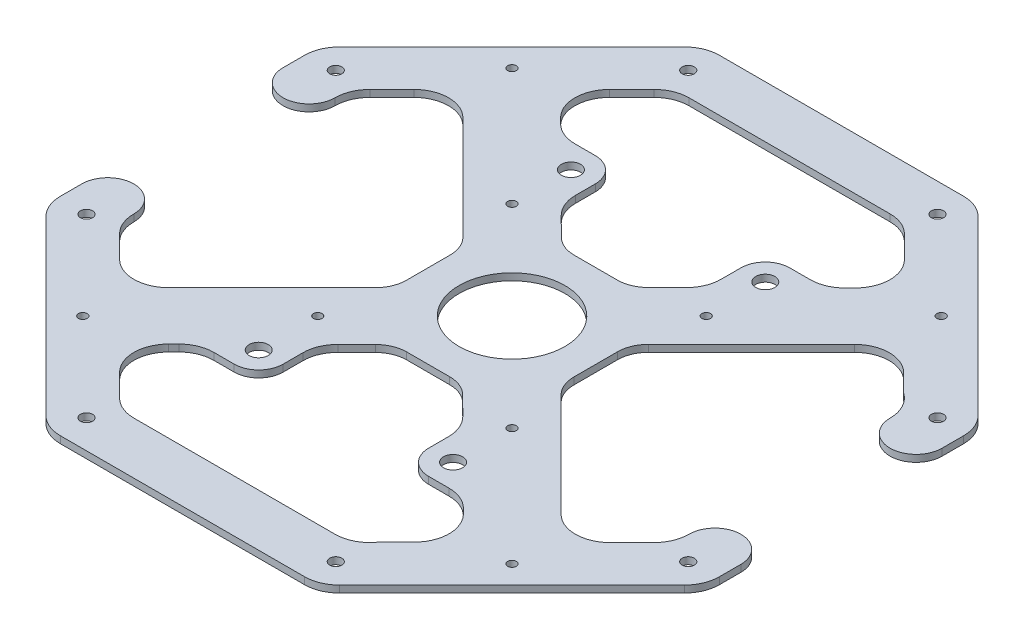
SolidWorks part; units mm, degrees
material "Hexcel AS4C (3000 Filaments)"
ref_plane "Front Plane" through (0, 0, 0) normal (0, 0, 1) x (1, 0, 0)
ref_plane "Top Plane" through (0, 0, 0) normal (0, 1, 0) x (1, 0, 0)
ref_plane "Right Plane" through (0, 0, 0) normal (1, 0, 0) x (0, 0, -1)
sketch "Sketch2" plane through (0, 0, 0) normal (0, 1, 0) x (1, 0, 0)
  line L0 (42.4939, 70.6432) -> (36.066, 77.0711)
  line L1 (92.0711, 42.2792) -> (42.2792, 92.0711)
  line L2 (35.2082, 95) -> (-35.2082, 95)
  line L3 (-42.2792, 92.0711) -> (-92.0711, 42.2792)
  line L4 (-95, 35.2082) -> (-95, -35.2082)
  line L5 (-92.0711, -42.2792) -> (-42.2792, -92.0711)
  line L6 (-35.2082, -95) -> (35.2082, -95)
  line L7 (42.2792, -92.0711) -> (92.0711, -42.2792)
  line L8 (95, -35.2082) -> (95, 35.2082)
  line L9 (28.9949, 80) -> (-28.9949, 80)
  line L10 (-70.7107, 42.4264) -> (-77.0711, 36.066)
  line L11 (-80, 28.9949) -> (-80, -28.9949)
  line L12 (-42.4939, -70.6432) -> (-36.066, -77.0711)
  line L13 (-28.9949, -80) -> (28.9949, -80)
  line L14 (70.7107, -42.4264) -> (77.0711, -36.066)
  line L15 (80, -28.9949) -> (80, 28.9949)
  line L68 (-80, 33.1371) -> (-80, -33.1371) construction
  line L69 (-80, -33.1371) -> (-33.1371, -80) construction
  line L70 (-33.1371, -80) -> (33.1371, -80) construction
  line L71 (33.1371, -80) -> (80, -33.1371) construction
  line L72 (80, -33.1371) -> (80, 33.1371) construction
  line L73 (80, 33.1371) -> (33.1371, 80) construction
  line L74 (33.1371, 80) -> (-33.1371, 80) construction
  line L75 (-33.1371, 80) -> (-80, 33.1371) construction
  line L76 (-95, 39.3503) -> (-95, -39.3503) construction
  line L77 (-95, -39.3503) -> (-39.3503, -95) construction
  line L78 (-39.3503, -95) -> (39.3503, -95) construction
  line L79 (39.3503, -95) -> (95, -39.3503) construction
  line L80 (95, -39.3503) -> (95, 39.3503) construction
  line L81 (95, 39.3503) -> (39.3503, 95) construction
  line L82 (39.3503, 95) -> (-39.3503, 95) construction
  line L83 (-39.3503, 95) -> (-95, 39.3503) construction
  line L84 (-26.7774, 12.6353) -> (-56.5685, 42.4264)
  line L94 (26.7797, 12.6376) -> (56.4684, 42.3047)
  line L97 (26.7774, -12.6353) -> (56.5685, -42.4264)
  line L98 (-26.7774, -12.6353) -> (-56.5685, -42.4264)
  line L100 (-6.2061, 24.1555) -> (6.2061, 24.1555)
  line L101 (24.1421, 6.2731) -> (24.1421, -6.2731)
  line L102 (6.1984, -24.1478) -> (-6.1984, -24.1478)
  line L103 (-24.1421, -6.2731) -> (-24.1421, 6.2731)
  line L104 (-36.0658, 77.0713) -> (-42.4938, 70.6436)
  line L105 (75.6946, 37.2152) -> (70.6082, 42.3019)
  line L106 (37.2161, -75.6933) -> (42.3807, -70.5289)
  line L107 (-77.0181, -36.1186) -> (-70.7109, -42.4262)
  line L122 (12.6353, 26.7774) -> (42.4264, 56.5685) [skipped]
  line L123 (-42.488, 56.4952) -> (-40.9723, 54.9821)
  line L124 (-18.0186, 32.2022) -> (-12.5953, 26.818)
  line L126 (-12.6353, -26.7774) -> (-42.4264, -56.5685) [skipped]
  line L130 (-33.4824, 49.4648) -> (-33.6643, 49.2416)
  line L131 (-23.5101, 39.5974) -> (-23.7772, 39.3284)
  line L132 (0, 0) -> (0, 34.9622)
  line L133 (0, 0) -> (56.5685, 0)
  line L140 (-23.5101, -39.5974) -> (-23.7772, -39.3284)
  line L141 (-33.4824, -49.4648) -> (-33.6643, -49.2416)
  line L142 (23.7772, -39.3284) -> (23.5101, -39.5974)
  line L143 (33.4824, -49.4648) -> (33.6643, -49.2416)
  line L144 (33.4824, 49.4648) -> (33.6643, 49.2416)
  line L145 (23.7772, 39.3284) -> (23.5101, 39.5974)
  line L146 (-20.9732, 45.0122) -> (-20.9732, 39.2988)
  line L147 (-28.0202, 52.0592) -> (-33.9073, 52.0592)
  line L148 (20.9732, 45.0122) -> (20.9732, 39.2988)
  line L149 (28.0202, 52.0592) -> (33.9073, 52.0592)
  line L150 (28.0202, -52.0592) -> (33.9073, -52.0592)
  line L151 (20.9732, -45.0122) -> (20.9732, -39.2988)
  line L152 (-28.0202, -52.0592) -> (-33.9073, -52.0592)
  line L153 (-20.9732, -45.0122) -> (-20.9732, -39.2988)
  line L154 (18.0186, 32.2022) -> (12.5953, 26.818)
  line L155 (40.9723, 54.9821) -> (42.488, 56.4952)
  line L156 (18.0186, -32.2022) -> (12.5953, -26.818)
  line L157 (40.9723, -54.9821) -> (42.488, -56.4952)
  line L158 (-18.0186, -32.2022) -> (-12.5953, -26.818)
  line L159 (-40.9723, -54.9821) -> (-42.488, -56.4952)
  circle A0 centre (0, 0) radius 95 construction
  circle A1 centre (0, 0) radius 15.25
  arc A2 (-80, -28.9949) -> (-77.0181, -36.1186) centre (-70, -28.9949) ccw
  arc A3 (-36.066, -77.0711) -> (-28.9949, -80) centre (-28.9949, -70) ccw
  arc A4 (28.9949, -80) -> (37.2161, -75.6933) centre (28.9949, -70) ccw
  arc A5 (77.0711, -36.066) -> (80, -28.9949) centre (70, -28.9949) ccw
  arc A6 (75.6946, 37.2152) -> (80, 28.9949) centre (70, 28.9949) cw
  arc A7 (36.066, 77.0711) -> (28.9949, 80) centre (28.9949, 70) ccw
  arc A8 (-28.9949, 80) -> (-36.0658, 77.0713) centre (-28.9949, 70) ccw
  arc A9 (-77.0711, 36.066) -> (-80, 28.9949) centre (-70, 28.9949) ccw
  arc A10 (-95, -35.2082) -> (-92.0711, -42.2792) centre (-85, -35.2082) ccw
  arc A11 (-42.2792, -92.0711) -> (-35.2082, -95) centre (-35.2082, -85) ccw
  arc A12 (35.2082, -95) -> (42.2792, -92.0711) centre (35.2082, -85) ccw
  arc A13 (92.0711, -42.2792) -> (95, -35.2082) centre (85, -35.2082) ccw
  arc A14 (92.0711, 42.2792) -> (95, 35.2082) centre (85, 35.2082) cw
  arc A15 (42.2792, 92.0711) -> (35.2082, 95) centre (35.2082, 85) ccw
  arc A16 (-35.2082, 95) -> (-42.2792, 92.0711) centre (-35.2082, 85) ccw
  arc A17 (-92.0711, 42.2792) -> (-95, 35.2082) centre (-85, 35.2082) ccw
  arc A18 (-42.4939, -70.6432) -> (-42.488, -56.4952) centre (-35.4228, -63.5722) cw
  arc A19 (70.7107, -42.4264) -> (56.5685, -42.4264) centre (63.6396, -35.3553) cw
  arc A20 (42.4939, 70.6432) -> (42.488, 56.4952) centre (35.4228, 63.5722) cw
  arc A21 (-70.7107, 42.4264) -> (-56.5685, 42.4264) centre (-63.6396, 35.3553) cw
  arc A22 (-56.5685, -42.4264) -> (-70.7109, -42.4262) centre (-63.6396, -35.3553) cw
  arc A23 (42.488, -56.4952) -> (42.3807, -70.5289) centre (35.3099, -63.4576) cw
  arc A24 (56.4684, 42.3047) -> (70.6082, 42.3019) centre (63.5369, 35.231) cw
  arc A25 (-42.488, 56.4952) -> (-42.4938, 70.6436) centre (-35.423, 63.5724) cw
  arc A26 (-12.5953, -26.818) -> (-6.1984, -24.1478) centre (-6.1984, -33.1452) cw
  arc A27 (12.5953, -26.818) -> (6.1984, -24.1478) centre (6.1984, -33.1452) ccw
  arc A28 (26.7774, -12.6353) -> (24.1421, -6.2731) centre (33.1396, -6.2731) cw
  arc A29 (26.7797, 12.6376) -> (24.1421, 6.2731) centre (33.1396, 6.2731) ccw
  arc A30 (12.5953, 26.818) -> (6.2061, 24.1555) centre (6.2061, 33.153) cw
  arc A31 (-12.5953, 26.818) -> (-6.2061, 24.1555) centre (-6.2061, 33.153) ccw
  arc A32 (-26.7774, -12.6353) -> (-24.1421, -6.2731) centre (-33.1396, -6.2731) ccw
  arc A33 (-26.7774, 12.6353) -> (-24.1421, 6.2731) centre (-33.1396, 6.2731) cw
  circle A34 centre (-86.7388, 35.9284) radius 1.75
  circle A35 centre (-35.9284, 86.7388) radius 1.75
  circle A36 centre (35.9284, 86.7388) radius 1.75
  circle A37 centre (86.7388, 35.9284) radius 1.75
  circle A38 centre (86.7388, -35.9284) radius 1.75
  circle A39 centre (35.9284, -86.7388) radius 1.75
  circle A40 centre (-35.9284, -86.7388) radius 1.75
  circle A41 centre (-86.7388, -35.9284) radius 1.75
  circle A55 centre (-28, 28) radius 1.25
  circle A56 centre (-61.8718, 61.8718) radius 1.25
  circle A57 centre (61.8718, 61.8718) radius 1.25
  circle A58 centre (28, 28) radius 1.25
  circle A59 centre (61.8718, -61.8718) radius 1.25
  circle A60 centre (28, -28) radius 1.25
  circle A61 centre (-61.8718, -61.8718) radius 1.25
  circle A62 centre (-28, -28) radius 1.25
  circle A63 centre (-28.0202, 45.0122) radius 2.75
  circle A64 centre (28.0202, 45.0122) radius 2.75
  circle A65 centre (28.0202, -45.0122) radius 2.75
  circle A66 centre (-28.0202, -45.0122) radius 2.75
  arc A76 (-80, 28.9949) -> (-95, 28.9949) centre (-87.5, 28.9949) cw
  arc A77 (-80, -28.9949) -> (-95, -29.033) centre (-87.5, -29.0325) ccw
  arc A78 (95, 28.9949) -> (80, 28.9949) centre (87.5, 28.9949) cw
  arc A79 (95, -28.9949) -> (80, -28.9949) centre (87.5, -28.9949) ccw
  arc A92 (-33.4824, 49.4648) -> (-23.5101, 39.5974) centre (-28.0202, 45.0122) cw
  arc A93 (-23.7721, 37.9142) -> (-23.7772, 39.3284) centre (-23.0675, 38.6239) cw
  arc A94 (-35.1459, 49.1657) -> (-33.6643, 49.2416) centre (-34.4394, 49.8734) ccw
  arc A95 (23.7721, 37.9142) -> (23.7772, 39.3284) centre (23.0675, 38.6239) ccw
  arc A96 (35.1459, 49.1657) -> (33.6643, 49.2416) centre (34.4394, 49.8734) cw
  arc A97 (33.4824, 49.4648) -> (23.5101, 39.5974) centre (28.0202, 45.0122) ccw
  arc A98 (33.4824, -49.4648) -> (23.5101, -39.5974) centre (28.0202, -45.0122) cw
  arc A99 (-33.4824, -49.4648) -> (-23.5101, -39.5974) centre (-28.0202, -45.0122) ccw
  arc A100 (35.1459, -49.1657) -> (33.6643, -49.2416) centre (34.4394, -49.8734) ccw
  arc A101 (23.7721, -37.9142) -> (23.7772, -39.3284) centre (23.0675, -38.6239) cw
  arc A102 (-23.7721, -37.9142) -> (-23.7772, -39.3284) centre (-23.0675, -38.6239) ccw
  arc A103 (-35.1459, -49.1657) -> (-33.6643, -49.2416) centre (-34.4394, -49.8734) cw
  arc A104 (-18.0186, 32.2022) -> (-20.9732, 39.2988) centre (-10.9732, 39.2988) cw
  arc A105 (-40.9723, 54.9821) -> (-33.9073, 52.0592) centre (-33.9073, 62.0592) ccw
  arc A106 (18.0186, 32.2022) -> (20.9732, 39.2988) centre (10.9732, 39.2988) ccw
  arc A107 (40.9723, 54.9821) -> (33.9073, 52.0592) centre (33.9073, 62.0592) cw
  arc A108 (40.9723, -54.9821) -> (33.9073, -52.0592) centre (33.9073, -62.0592) ccw
  arc A109 (18.0186, -32.2022) -> (20.9732, -39.2988) centre (10.9732, -39.2988) cw
  arc A110 (-40.9723, -54.9821) -> (-33.9073, -52.0592) centre (-33.9073, -62.0592) cw
  arc A111 (-18.0186, -32.2022) -> (-20.9732, -39.2988) centre (-10.9732, -39.2988) ccw
  point P22 (0, 0)
  point P25 (0, 0)
  point P49 (0, 0)
  point P96 (0, 0)
  point P104 (-49.4975, 63.6396)
  point P105 (-0.1137, 0.0002)
  point P126 (-41.7302, 55.7387)
  point P142 (0, 0)
  point P150 (0, 0)
  point P159 (0, 0)
  point P169 (0, 0)
  point P187 (0, 0)
  point P194 (41.7302, 55.7387)
  point P204 (-28.0202, 45.0122)
  point P232 (0, 0)
  dimension "D2" = 10
  dimension "D4" = 10
  dimension "D5" = 10
  dimension "D6" = 8.9974
  dimension "D7" = 4
  dimension "D9" = 4
  dimension "D8" = 10
  dimension "D10" = 8
  dimension "D11" = 1
  dimension "D3" = 4
  dimension "D1" = 15
extrude "Boss-Extrude1" add sketch "Sketch2" along normal blind 2
